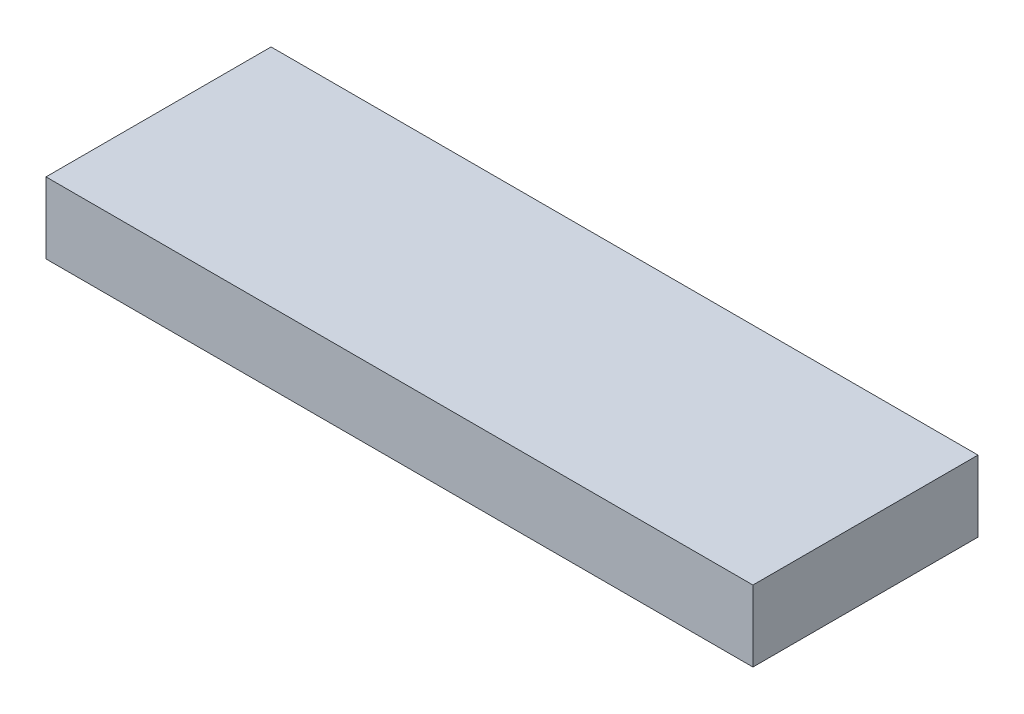
SolidWorks part; units mm, degrees
material "MDF"
ref_plane "Front Plane" through (0, 0, 0) normal (0, 0, 1) x (1, 0, 0)
ref_plane "Top Plane" through (0, 0, 0) normal (0, 1, 0) x (1, 0, 0)
ref_plane "Right Plane" through (0, 0, 0) normal (1, 0, 0) x (0, 0, -1)
sketch "Sketch1" plane through (0, 0, 0) normal (0, 0, 1) x (1, 0, 0)
  line L1 (133.8612, 0) -> (323.3388, 0)
  line L2 (133.8612, 0) -> (133.8612, -19.05)
  line L3 (133.8612, -19.05) -> (323.3388, -19.05)
  line L4 (323.3388, 0) -> (323.3388, -19.05)
  line L5 (323.3388, -298.45) -> (323.3388, 20.8246) construction
  line L6 (133.8612, -298.45) -> (133.8612, 20.8246) construction
  line L8 (456.6888, 0) -> (0.5112, 0) construction
  dimension "D1" = 19.05
extrude "Boss-Extrude1" add sketch "Sketch1" along normal up to surface (60.325 mm away)
hole_wizard "Hole1" positions "Sketch2" profile "Sketch3" legacy
sketch "Sketch2" plane through (228.6, 0, -25.4) normal (0, 0, -1) x (-1, 0, 0)
  line L0 (218.5638, 0) -> (218.5638, -437.642) construction
  line L4 (104.2638, 0) -> (104.2638, -298.45) construction
  line L13 (120.1388, -460.375) -> (120.1388, -311.15) construction
  line L16 (126.4888, -311.15) -> (113.7888, -311.15) construction
  line L18 (126.4888, -304.8) -> (-126.4888, -304.8) construction
  line L22 (94.7388, -276.225) -> (-94.7388, -276.225) construction
  line L24 (-94.7388, -285.75) -> (-94.7388, -266.7) construction
  line L26 (94.7388, -285.75) -> (94.7388, -266.7) construction
  line L27 (-94.7388, 0) -> (-94.7388, -19.05) construction
  line L29 (94.7388, 0) -> (94.7388, -19.05) construction
  line L31 (94.7388, -9.525) -> (-94.7388, -9.525) construction
  point P15 (218.5638, -31.75)
  point P17 (218.5638, -218.821)
  point P19 (218.5638, -418.592)
  point P28 (104.2638, -19.05)
  point P30 (104.2638, -149.225)
  point P32 (104.2638, -279.4)
  point P69 (120.1388, -330.2)
  point P71 (120.1388, -441.325)
  point P76 (-120.1388, -441.325)
  point P77 (-120.1388, -330.2)
  point P80 (-104.2638, -279.4)
  point P81 (-104.2638, -149.225)
  point P82 (-104.2638, -19.05)
  point P83 (-218.5638, -418.592)
  point P84 (-218.5638, -218.821)
  point P85 (-218.5638, -31.75)
  point P99 (0, -304.8)
  point P101 (107.4388, -304.8)
  point P103 (-107.4388, -304.8)
  point P127 (75.6888, -276.225)
  point P129 (0, -276.225)
  point P131 (-75.6888, -276.225)
  point P152 (75.6888, -9.525)
  point P154 (0, -9.525)
  point P156 (-75.6888, -9.525)
sketch "Sketch3" plane through (304.2888, -9.525, -25.4) normal (1, 0, 0) x (0, 1, 0)
  line L0 (0, 0) -> (0, 39.0539)
  line L1 (0, 39.0539) -> (1.5875, 38.1)
  line L2 (1.5875, 38.1) -> (1.5875, 4.0177)
  line L3 (1.5875, 4.0177) -> (5.08, 0)
  line L4 (5.08, 0) -> (0, 0)
  line L5 (0, -14.3089) -> (0, 102.4216) construction
  line L6 (0, 39.0539) -> (-1.5875, 38.1) construction
  line L7 (-1.5875, 4.0177) -> (-5.08, 0) construction
  dimension "Diameter" = 3.175
  dimension "Depth" = 38.1
  dimension "C-Sink Diameter" = 10.16
  dimension "C-Sink Angle" = 82
  dimension "Drill Angle" = 118
